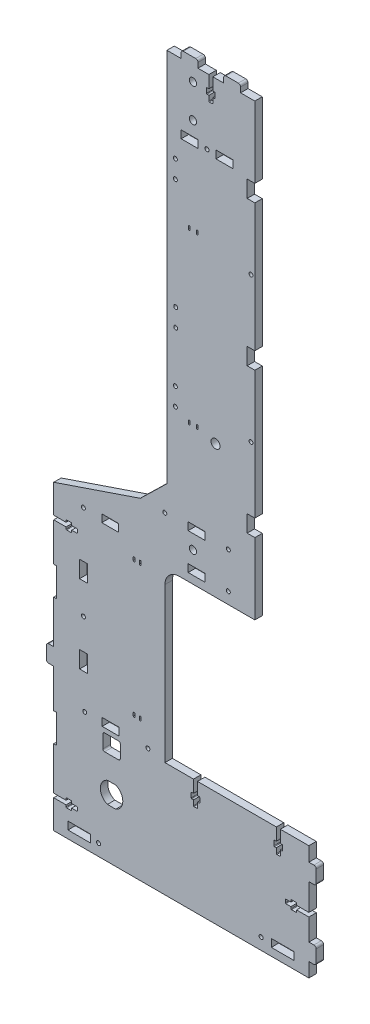
SolidWorks part; units mm, degrees
ref_plane "Front Plane" through (0, 0, 0) normal (0, 0, 1) x (1, 0, 0)
ref_plane "Top Plane" through (0, 0, 0) normal (0, 1, 0) x (1, 0, 0)
ref_plane "Right Plane" through (0, 0, 0) normal (1, 0, 0) x (0, 0, -1)
sketch "Model" plane through (0, 0, 0) normal (0, 0, 1) x (1, 0, 0)
  line L0 (-34.58, 345.05) -> (-19.58, 345.05)
  line L1 (-34.58, 338.17) -> (-34.58, 345.05)
  line L2 (-19.58, 338.17) -> (-34.58, 338.17)
  line L3 (-19.58, 338.17) -> (-19.58, 345.05)
  line L4 (14.65, -238.23) -> (14.65, -245.11)
  line L5 (34.65, -245.11) -> (14.65, -245.11)
  line L6 (34.65, -238.23) -> (34.65, -245.11)
  line L7 (14.65, -238.23) -> (34.65, -238.23)
  line L8 (-166.35, -238.23) -> (-166.35, -245.11)
  line L9 (-146.35, -245.11) -> (-166.35, -245.11)
  line L10 (-146.35, -238.23) -> (-146.35, -245.11)
  line L11 (-146.35, -238.23) -> (-166.35, -238.23)
  line L12 (-121.25, 6.88) -> (-121.25, 13.74)
  line L13 (-121.25, 13.74) -> (-136.25, 13.74)
  line L14 (-136.25, 6.88) -> (-136.25, 13.74)
  line L15 (-136.25, 6.88) -> (-121.25, 6.88)
  line L16 (-50.6, 338.17) -> (-50.6, 345.05)
  line L17 (-65.6, 345.05) -> (-50.6, 345.05)
  line L18 (-65.6, 338.17) -> (-65.6, 345.05)
  line L19 (-65.6, 338.17) -> (-50.6, 338.17)
  line L20 (-44.38, 6.88) -> (-44.38, 13.74)
  line L21 (-59.38, 13.74) -> (-44.38, 13.74)
  line L22 (-59.38, 6.88) -> (-59.38, 13.74)
  line L23 (-59.38, 6.88) -> (-44.38, 6.88)
  line L24 (48.1, -177.69) -> (52.6, -177.69)
  line L25 (48.1, -201.44) -> (48.1, -177.69)
  line L26 (48.1, -201.44) -> (37.1, -201.44)
  line L27 (37.1, -201.44) -> (37.1, -199.855)
  line L28 (36.6, -199.355) -> (32.6, -199.355)
  line L29 (32.1, -199.855) -> (32.1, -201.44)
  line L30 (32.1, -201.44) -> (27.6, -201.44)
  line L31 (27.1, -201.94) -> (27.1, -204.49)
  line L32 (27.6, -204.99) -> (32.1, -204.99)
  line L33 (32.1, -204.99) -> (32.1, -206.575)
  line L34 (32.6, -207.075) -> (36.6, -207.075)
  line L35 (37.1, -206.575) -> (37.1, -204.99)
  line L36 (37.1, -204.99) -> (48.1, -204.99)
  line L37 (48.1, -224.29) -> (52.6, -224.29)
  line L38 (54.6, -226.29) -> (54.6, -237.29)
  line L39 (48.1, -239.29) -> (52.6, -239.29)
  line L40 (48.1, -251.99) -> (48.1, -239.29)
  line L41 (-179.05, -251.99) -> (48.1, -251.99)
  line L42 (-179.05, -226.59) -> (-179.05, -251.99)
  line L43 (-179.05, -226.59) -> (-168.05, -226.59)
  line L44 (-168.05, -226.59) -> (-168.05, -228.175)
  line L45 (-167.55, -228.675) -> (-163.55, -228.675)
  line L46 (-163.05, -228.175) -> (-163.05, -226.59)
  line L47 (-163.05, -226.59) -> (-158.55, -226.59)
  line L48 (-158.05, -226.09) -> (-158.05, -223.54)
  line L49 (-158.55, -223.04) -> (-163.05, -223.04)
  line L50 (-163.05, -223.04) -> (-163.05, -221.455)
  line L51 (-163.55, -220.955) -> (-167.55, -220.955)
  line L52 (-168.05, -221.455) -> (-168.05, -223.04)
  line L53 (-168.05, -223.04) -> (-179.05, -223.04)
  line L54 (-179.05, -184.93) -> (-176.35, -184.93)
  line L55 (-176.35, -184.93) -> (-176.35, -159.53)
  line L56 (-176.35, -159.53) -> (-179.05, -159.53)
  line L57 (-179.05, -125.17) -> (-183.55, -125.17)
  line L58 (-185.55, -112.17) -> (-185.55, -123.17)
  line L59 (-179.05, -110.17) -> (-183.55, -110.17)
  line L60 (-179.05, -71.93) -> (-176.35, -71.93)
  line L61 (-176.35, -71.93) -> (-176.35, -46.53)
  line L62 (-176.35, -46.53) -> (-179.05, -46.53)
  line L63 (-179.05, -12.3) -> (-179.05, -46.53)
  line L64 (-179.05, -12.3) -> (-168.05, -12.3)
  line L65 (-168.05, -12.3) -> (-168.05, -13.885)
  line L66 (-167.55, -14.385) -> (-163.55, -14.385)
  line L67 (-163.05, -13.885) -> (-163.05, -12.3)
  line L68 (-163.05, -12.3) -> (-158.55, -12.3)
  line L69 (-158.05, -11.8) -> (-158.05, -9.25)
  line L70 (-158.55, -8.75) -> (-163.05, -8.75)
  line L71 (-163.05, -8.75) -> (-163.05, -7.165)
  line L72 (-163.55, -6.665) -> (-167.55, -6.665)
  line L73 (-168.05, -7.165) -> (-168.05, -8.75)
  line L74 (-168.05, -8.75) -> (-179.05, -8.75)
  line L75 (-179.05, 16.65) -> (-179.05, -8.75)
  line L76 (-101.9733, 42.814) -> (-179.05, 16.65)
  line L77 (-78.3, 65.85) -> (-101.9733, 42.814)
  line L78 (-78.3, 400.05) -> (-78.3, 65.85)
  line L79 (-65.6, 400.05) -> (-65.6, 404.55)
  line L80 (-63.6, 406.55) -> (-52.6, 406.55)
  line L81 (-50.6, 400.05) -> (-50.6, 404.55)
  line L82 (-40.925, 400.05) -> (-50.6, 400.05)
  line L83 (-40.925, 400.05) -> (-40.925, 389.05)
  line L84 (-40.925, 389.05) -> (-42.51, 389.05)
  line L85 (-43.01, 388.55) -> (-43.01, 384.55)
  line L86 (-42.51, 384.05) -> (-40.925, 384.05)
  line L87 (-40.925, 384.05) -> (-40.925, 379.55)
  line L88 (-40.425, 379.05) -> (-37.875, 379.05)
  line L89 (-37.375, 379.55) -> (-37.375, 384.05)
  line L90 (-37.375, 384.05) -> (-35.79, 384.05)
  line L91 (-35.29, 384.55) -> (-35.29, 388.55)
  line L92 (-35.79, 389.05) -> (-37.375, 389.05)
  line L93 (-37.375, 389.05) -> (-37.375, 400.05)
  line L94 (-27.7, 400.05) -> (-27.7, 404.55)
  line L95 (-25.7, 406.55) -> (-14.7, 406.55)
  line L96 (-12.7, 400.05) -> (-12.7, 404.55)
  line L97 (0, 400.05) -> (-12.7, 400.05)
  line L98 (0, 336.55) -> (0, 400.05)
  line L99 (-6.86, 336.55) -> (0, 336.55)
  line L100 (-6.86, 336.55) -> (-6.86, 321.55)
  line L101 (-6.86, 321.55) -> (0, 321.55)
  line L102 (0, 207.525) -> (0, 321.55)
  line L103 (-6.86, 207.525) -> (0, 207.525)
  line L104 (-6.86, 207.525) -> (-6.86, 192.525)
  line L105 (-6.86, 192.525) -> (0, 192.525)
  line L106 (0, 78.5) -> (0, 192.525)
  line L107 (-6.86, 78.5) -> (0, 78.5)
  line L108 (-6.86, 78.5) -> (-6.86, 63.5)
  line L109 (-6.86, 63.5) -> (0, 63.5)
  line L110 (0, 0) -> (0, 63.5)
  line L111 (-67.3, 0) -> (0, 0)
  line L112 (-80, -149.99) -> (-80, -12.7)
  line L113 (-54.6, -149.99) -> (-80, -149.99)
  line L114 (-54.6, -149.99) -> (-54.6, -160.99)
  line L115 (-54.6, -160.99) -> (-56.185, -160.99)
  line L116 (-56.685, -161.49) -> (-56.685, -165.49)
  line L117 (-56.185, -165.99) -> (-54.6, -165.99)
  line L118 (-54.6, -165.99) -> (-54.6, -170.49)
  line L119 (-54.1, -170.99) -> (-51.55, -170.99)
  line L120 (-51.05, -170.49) -> (-51.05, -165.99)
  line L121 (-51.05, -165.99) -> (-49.465, -165.99)
  line L122 (-48.965, -165.49) -> (-48.965, -161.49)
  line L123 (-49.465, -160.99) -> (-51.05, -160.99)
  line L124 (-51.05, -160.99) -> (-51.05, -149.99)
  line L125 (19.15, -149.99) -> (-51.05, -149.99)
  line L126 (19.15, -149.99) -> (19.15, -160.99)
  line L127 (19.15, -160.99) -> (17.565, -160.99)
  line L128 (17.065, -161.49) -> (17.065, -165.49)
  line L129 (17.565, -165.99) -> (19.15, -165.99)
  line L130 (19.15, -165.99) -> (19.15, -170.49)
  line L131 (19.65, -170.99) -> (22.2, -170.99)
  line L132 (22.7, -170.49) -> (22.7, -165.99)
  line L133 (22.7, -165.99) -> (24.285, -165.99)
  line L134 (24.785, -165.49) -> (24.785, -161.49)
  line L135 (24.285, -160.99) -> (22.7, -160.99)
  line L136 (22.7, -160.99) -> (22.7, -149.99)
  line L137 (48.1, -149.99) -> (22.7, -149.99)
  line L138 (48.1, -162.69) -> (52.6, -162.69)
  line L139 (54.6, -164.69) -> (54.6, -175.69)
  line L140 (-44.38, 39.14) -> (-44.38, 46)
  line L141 (-59.38, 46) -> (-44.38, 46)
  line L142 (-59.38, 39.14) -> (-59.38, 46)
  line L143 (-59.38, 39.14) -> (-44.38, 39.14)
  line L144 (-120.9, -149.99) -> (-120.9, -143.13)
  line L145 (-135.9, -143.13) -> (-120.9, -143.13)
  line L146 (-135.9, -149.99) -> (-135.9, -143.13)
  line L147 (-135.9, -149.99) -> (-120.9, -149.99)
  line L148 (-156.05, -31.22) -> (-156.05, -46.22)
  line L149 (-156.05, -46.22) -> (-149.17, -46.22)
  line L150 (-149.17, -46.22) -> (-149.17, -31.22)
  line L151 (-149.17, -31.22) -> (-156.05, -31.22)
  line L152 (-156.05, -100.82) -> (-156.05, -115.82)
  line L153 (-156.05, -115.82) -> (-149.17, -115.82)
  line L154 (-149.17, -115.82) -> (-149.17, -100.82)
  line L155 (-149.17, -100.82) -> (-156.05, -100.82)
  line L156 (-135.29, -155.4588) -> (-135.29, -167.0087)
  line L157 (-133.79, -168.5087) -> (-121.31, -168.5087)
  line L158 (-119.81, -167.0087) -> (-119.81, -155.4588)
  line L159 (-121.31, -153.9588) -> (-133.79, -153.9588)
  line L160 (-123.8744, -189.2088) -> (-131.2256, -189.2088)
  line L161 (-131.2256, -207.8088) -> (-123.8744, -207.8088)
  line L162 (-57.55, 271.85) -> (-57.55, 274.25)
  line L163 (-59.05, 274.25) -> (-59.05, 271.85)
  line L164 (-50.55, 271.85) -> (-50.55, 274.25)
  line L165 (-52.05, 274.25) -> (-52.05, 271.85)
  line L166 (-57.55, 121.85) -> (-57.55, 124.25)
  line L167 (-59.05, 124.25) -> (-59.05, 121.85)
  line L168 (-50.55, 121.85) -> (-50.55, 124.25)
  line L169 (-52.05, 124.25) -> (-52.05, 121.85)
  line L170 (-106.75, -128.13) -> (-106.75, -125.73)
  line L171 (-108.25, -125.73) -> (-108.25, -128.13)
  line L172 (-101.25, -128.13) -> (-101.25, -125.73)
  line L173 (-102.75, -125.73) -> (-102.75, -128.13)
  line L174 (-106.75, -8.13) -> (-106.75, -5.73)
  line L175 (-108.25, -5.73) -> (-108.25, -8.13)
  line L176 (-101.25, -8.13) -> (-101.25, -5.73)
  line L177 (-102.75, -5.73) -> (-102.75, -8.13)
  line L178 (-179.05, -71.93) -> (-179.05, -110.17)
  line L179 (-179.05, -184.93) -> (-179.05, -223.04)
  line L180 (48.1, -162.69) -> (48.1, -149.99)
  line L181 (48.1, -224.29) -> (48.1, -204.99)
  line L182 (-179.05, -125.17) -> (-179.05, -159.53)
  line L183 (-65.6, 400.05) -> (-78.3, 400.05)
  line L184 (-27.7, 400.05) -> (-37.375, 400.05)
  circle A0 centre (-42.59, 341.61) radius 1.775
  circle A1 centre (-151.415, -146.56) radius 1.775
  circle A2 centre (5.575, -241.67) radius 1.775
  circle A3 centre (-139.175, -241.67) radius 1.775
  circle A4 centre (-95.225, -146.56) radius 1.775
  circle A5 centre (-80.155, 42.57) radius 1.775
  circle A6 centre (-23.605, 42.57) radius 1.775
  circle A7 centre (-23.605, 10.31) radius 1.775
  circle A8 centre (-3.43, 135.5125) radius 1.775
  circle A9 centre (-3.43, 264.5375) radius 1.775
  circle A10 centre (-152.61, 10.31) radius 1.775
  circle A11 centre (-152.61, -73.52) radius 1.775
  circle A12 centre (-55.1252, 26.44) radius 3.25
  circle A13 centre (-55.1252, 357.75) radius 3.25
  circle A14 centre (-55.1252, 387.35) radius 3.25
  circle A15 centre (-70.7592, 129.0125) radius 1.775
  circle A16 centre (-70.7592, 144.8875) radius 1.775
  circle A17 centre (-70.7592, 304.4125) radius 1.775
  circle A18 centre (-70.7592, 320.2875) radius 1.775
  circle A19 centre (-34.9881, 118.3747) radius 4
  circle A20 centre (-70.41, 205.9875) radius 1.775
  circle A21 centre (-70.41, 190.1125) radius 1.775
  arc A22 (52.6, -177.69) -> (54.6, -175.69) centre (52.6, -175.69) ccw
  arc A23 (37.1, -199.855) -> (36.6, -199.355) centre (36.6, -199.855) ccw
  arc A24 (32.6, -199.355) -> (32.1, -199.855) centre (32.6, -199.855) ccw
  arc A25 (27.6, -201.44) -> (27.1, -201.94) centre (27.6, -201.94) ccw
  arc A26 (27.1, -204.49) -> (27.6, -204.99) centre (27.6, -204.49) ccw
  arc A27 (32.1, -206.575) -> (32.6, -207.075) centre (32.6, -206.575) ccw
  arc A28 (36.6, -207.075) -> (37.1, -206.575) centre (36.6, -206.575) ccw
  arc A29 (54.6, -226.29) -> (52.6, -224.29) centre (52.6, -226.29) ccw
  arc A30 (52.6, -239.29) -> (54.6, -237.29) centre (52.6, -237.29) ccw
  arc A31 (-168.05, -228.175) -> (-167.55, -228.675) centre (-167.55, -228.175) ccw
  arc A32 (-163.55, -228.675) -> (-163.05, -228.175) centre (-163.55, -228.175) ccw
  arc A33 (-158.55, -226.59) -> (-158.05, -226.09) centre (-158.55, -226.09) ccw
  arc A34 (-158.05, -223.54) -> (-158.55, -223.04) centre (-158.55, -223.54) ccw
  arc A35 (-163.05, -221.455) -> (-163.55, -220.955) centre (-163.55, -221.455) ccw
  arc A36 (-167.55, -220.955) -> (-168.05, -221.455) centre (-167.55, -221.455) ccw
  arc A37 (-185.55, -123.17) -> (-183.55, -125.17) centre (-183.55, -123.17) ccw
  arc A38 (-183.55, -110.17) -> (-185.55, -112.17) centre (-183.55, -112.17) ccw
  arc A39 (-168.05, -13.885) -> (-167.55, -14.385) centre (-167.55, -13.885) ccw
  arc A40 (-163.55, -14.385) -> (-163.05, -13.885) centre (-163.55, -13.885) ccw
  arc A41 (-158.55, -12.3) -> (-158.05, -11.8) centre (-158.55, -11.8) ccw
  arc A42 (-158.05, -9.25) -> (-158.55, -8.75) centre (-158.55, -9.25) ccw
  arc A43 (-163.05, -7.165) -> (-163.55, -6.665) centre (-163.55, -7.165) ccw
  arc A44 (-167.55, -6.665) -> (-168.05, -7.165) centre (-167.55, -7.165) ccw
  arc A45 (-63.6, 406.55) -> (-65.6, 404.55) centre (-63.6, 404.55) ccw
  arc A46 (-50.6, 404.55) -> (-52.6, 406.55) centre (-52.6, 404.55) ccw
  arc A47 (-42.51, 389.05) -> (-43.01, 388.55) centre (-42.51, 388.55) ccw
  arc A48 (-43.01, 384.55) -> (-42.51, 384.05) centre (-42.51, 384.55) ccw
  arc A49 (-40.925, 379.55) -> (-40.425, 379.05) centre (-40.425, 379.55) ccw
  arc A50 (-37.875, 379.05) -> (-37.375, 379.55) centre (-37.875, 379.55) ccw
  arc A51 (-35.79, 384.05) -> (-35.29, 384.55) centre (-35.79, 384.55) ccw
  arc A52 (-35.29, 388.55) -> (-35.79, 389.05) centre (-35.79, 388.55) ccw
  arc A53 (-25.7, 406.55) -> (-27.7, 404.55) centre (-25.7, 404.55) ccw
  arc A54 (-12.7, 404.55) -> (-14.7, 406.55) centre (-14.7, 404.55) ccw
  arc A55 (-67.3, 0) -> (-80, -12.7) centre (-67.3, -12.7) ccw
  arc A56 (-56.185, -160.99) -> (-56.685, -161.49) centre (-56.185, -161.49) ccw
  arc A57 (-56.685, -165.49) -> (-56.185, -165.99) centre (-56.185, -165.49) ccw
  arc A58 (-54.6, -170.49) -> (-54.1, -170.99) centre (-54.1, -170.49) ccw
  arc A59 (-51.55, -170.99) -> (-51.05, -170.49) centre (-51.55, -170.49) ccw
  arc A60 (-49.465, -165.99) -> (-48.965, -165.49) centre (-49.465, -165.49) ccw
  arc A61 (-48.965, -161.49) -> (-49.465, -160.99) centre (-49.465, -161.49) ccw
  arc A62 (17.565, -160.99) -> (17.065, -161.49) centre (17.565, -161.49) ccw
  arc A63 (17.065, -165.49) -> (17.565, -165.99) centre (17.565, -165.49) ccw
  arc A64 (19.15, -170.49) -> (19.65, -170.99) centre (19.65, -170.49) ccw
  arc A65 (22.2, -170.99) -> (22.7, -170.49) centre (22.2, -170.49) ccw
  arc A66 (24.285, -165.99) -> (24.785, -165.49) centre (24.285, -165.49) ccw
  arc A67 (24.785, -161.49) -> (24.285, -160.99) centre (24.285, -161.49) ccw
  arc A68 (54.6, -164.69) -> (52.6, -162.69) centre (52.6, -164.69) ccw
  arc A69 (-133.79, -153.9588) -> (-135.29, -155.4588) centre (-133.79, -155.4588) ccw
  arc A70 (-135.29, -167.0087) -> (-133.79, -168.5087) centre (-133.79, -167.0087) ccw
  arc A71 (-121.31, -168.5087) -> (-119.81, -167.0087) centre (-121.31, -167.0087) ccw
  arc A72 (-119.81, -155.4588) -> (-121.31, -153.9588) centre (-121.31, -155.4588) ccw
  arc A73 (-123.8744, -207.8088) -> (-123.8744, -189.2088) centre (-127.55, -198.5088) ccw
  arc A74 (-131.2256, -189.2088) -> (-131.2256, -207.8088) centre (-127.55, -198.5088) ccw
  arc A75 (-59.05, 271.85) -> (-57.55, 271.85) centre (-58.3, 271.85) ccw
  arc A76 (-57.55, 274.25) -> (-59.05, 274.25) centre (-58.3, 274.25) ccw
  arc A77 (-52.05, 271.85) -> (-50.55, 271.85) centre (-51.3, 271.85) ccw
  arc A78 (-50.55, 274.25) -> (-52.05, 274.25) centre (-51.3, 274.25) ccw
  arc A79 (-59.05, 121.85) -> (-57.55, 121.85) centre (-58.3, 121.85) ccw
  arc A80 (-57.55, 124.25) -> (-59.05, 124.25) centre (-58.3, 124.25) ccw
  arc A81 (-52.05, 121.85) -> (-50.55, 121.85) centre (-51.3, 121.85) ccw
  arc A82 (-50.55, 124.25) -> (-52.05, 124.25) centre (-51.3, 124.25) ccw
  arc A83 (-108.25, -128.13) -> (-106.75, -128.13) centre (-107.5, -128.13) ccw
  arc A84 (-106.75, -125.73) -> (-108.25, -125.73) centre (-107.5, -125.73) ccw
  arc A85 (-102.75, -128.13) -> (-101.25, -128.13) centre (-102, -128.13) ccw
  arc A86 (-101.25, -125.73) -> (-102.75, -125.73) centre (-102, -125.73) ccw
  arc A87 (-108.25, -8.13) -> (-106.75, -8.13) centre (-107.5, -8.13) ccw
  arc A88 (-106.75, -5.73) -> (-108.25, -5.73) centre (-107.5, -5.73) ccw
  arc A89 (-102.75, -8.13) -> (-101.25, -8.13) centre (-102, -8.13) ccw
  arc A90 (-101.25, -5.73) -> (-102.75, -5.73) centre (-102, -5.73) ccw
extrude "Boss-Extrude1" add sketch "Model" along normal blind 6.6
